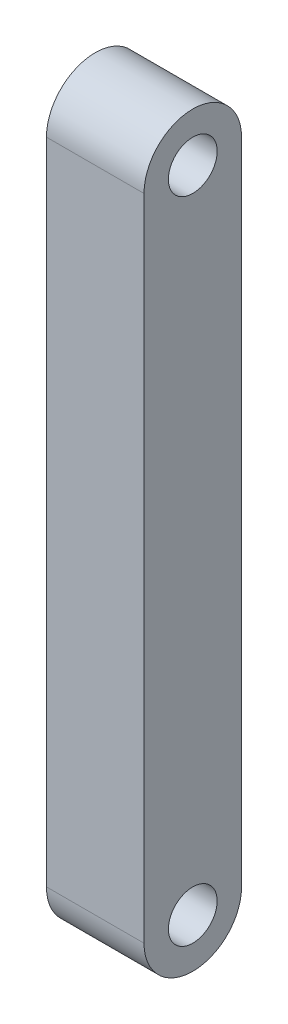
SolidWorks part; units mm, degrees
ref_plane "Front Plane" through (0, 0, 0) normal (0, 0, 1) x (1, 0, 0)
ref_plane "Top Plane" through (0, 0, 0) normal (0, 1, 0) x (1, 0, 0)
ref_plane "Right Plane" through (0, 0, 0) normal (1, 0, 0) x (0, 0, -1)
sketch "Sketch1" plane through (0, 0, 0) normal (1, 0, 0) x (0, 0, -1)
  line L0 (1.6188, -13.31) -> (1.6188, 13.31) construction
  line L1 (1.6188, -13.31) -> (1.6188, 13.31) construction
  line L2 (-0.3812, -13.31) -> (-0.3812, 13.31)
  line L3 (1.6188, 13.31) -> (-6.8909, 8.0579) construction
  line L4 (-6.8909, 8.0579) -> (1.6188, -13.31) construction
  line L5 (-6.8909, 8.0579) -> (1.6188, -13.31) construction
  line L6 (3.6188, -13.31) -> (3.6188, 13.31)
  line L8 (-6.8909, 8.0579) -> (1.6188, 13.31) construction
  arc A0 (-0.3812, -13.31) -> (3.6188, -13.31) centre (1.6188, -13.31) ccw
  arc A1 (3.6188, 13.31) -> (-0.3812, 13.31) centre (1.6188, 13.31) ccw
  circle A2 centre (1.6188, 13.31) radius 1
  circle A3 centre (1.6188, -13.31) radius 1
  point P0 (1.6188, 0)
  point P18 (-4.2548, 10.6839)
  dimension "D3" = 2
  dimension "D4" = 2
  dimension "D1" = 26.62
  dimension "D2" = 4
  dimension "D5" = 10
extrude "Boss-Extrude1" add sketch "Sketch1" along normal blind 4
